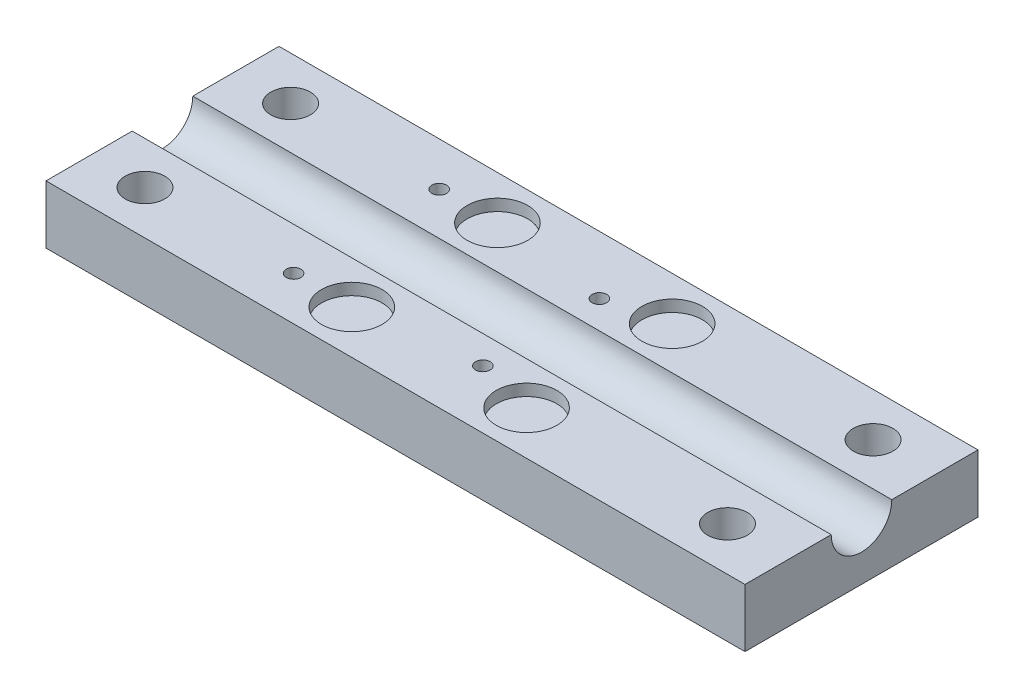
SolidWorks part; units mm, degrees
ref_plane "Front Plane" through (0, 0, 0) normal (0, 0, 1) x (1, 0, 0)
ref_plane "Top Plane" through (0, 0, 0) normal (0, 1, 0) x (1, 0, 0)
ref_plane "Right Plane" through (0, 0, 0) normal (1, 0, 0) x (0, 0, -1)
sketch "Sketch1" plane through (0, 0, 0) normal (0, 1, 0) x (1, 0, 0)
  line L1 (-38.1, 12.7) -> (38.1, 12.7)
  line L2 (-38.1, 12.7) -> (-38.1, -12.7)
  line L3 (-38.1, -12.7) -> (38.1, -12.7)
  line L4 (38.1, 12.7) -> (38.1, -12.7)
  dimension "D1" = 25.4
  dimension "D2" = 76.2
  dimension "D3" = 38.1
  dimension "D4" = 12.7
extrude "Boss-Extrude1" add sketch "Sketch1" along normal blind 6.35
sketch "Sketch2" plane through (0, 6.35, 0) normal (0, 1, 0) x (1, 0, 0)
  circle A0 centre (-32.0741, 7.9375) radius 2.159
  circle A1 centre (-32.0741, -7.9375) radius 2.159
  circle A2 centre (31.4259, 7.9375) radius 2.159
  circle A3 centre (31.4259, -7.9375) radius 2.159
  dimension "D1" = 4.318
  dimension "D2" = 15.875
  dimension "D3" = 63.5
  dimension "D4" = 32.0741
  dimension "D5" = 7.9375
extrude "Cut-Extrude1" cut sketch "Sketch2" against normal through all
sketch "Sketch3" plane through (0, 6.35, 0) normal (0, 1, 0) x (1, 0, 0)
  circle A0 centre (-9.525, 7.9375) radius 3.302
  circle A1 centre (-9.525, -7.9375) radius 3.302
  circle A2 centre (9.525, -7.9375) radius 3.302
  circle A3 centre (9.525, 7.9375) radius 3.302
  dimension "D1" = 6.604
  dimension "D2" = 15.875
  dimension "D3" = 19.05
  dimension "D4" = 7.9375
  dimension "D5" = 9.525
extrude "Cut-Extrude2" cut sketch "Sketch3" against normal blind 1.27
sketch "Sketch4" plane through (0, 6.35, 0) normal (0, 1, 0) x (1, 0, 0)
  circle A0 centre (-15.875, 7.9375) radius 0.7937
  circle A1 centre (-15.875, -7.9375) radius 0.7937
  circle A2 centre (3.175, 6.35) radius 0.7937
  circle A3 centre (3.175, -6.35) radius 0.7938
  dimension "D1" = 1.5875
  dimension "D2" = 15.875
  dimension "D3" = 7.9375
  dimension "D4" = 15.875
  dimension "D5" = 12.7
  dimension "D6" = 6.35
  dimension "D7" = 3.175
extrude "Cut-Extrude3" cut sketch "Sketch4" against normal through all
sketch "Sketch5" plane through (-38.1, 0, 0) normal (-1, 0, 0) x (0, 0, 1)
  line L0 (-12.7, 6.35) -> (12.7, 6.35) construction
  circle A0 centre (0, 6.35) radius 3.302
  dimension "D1" = 6.604
extrude "Cut-Extrude4" cut sketch "Sketch5" against normal through all
